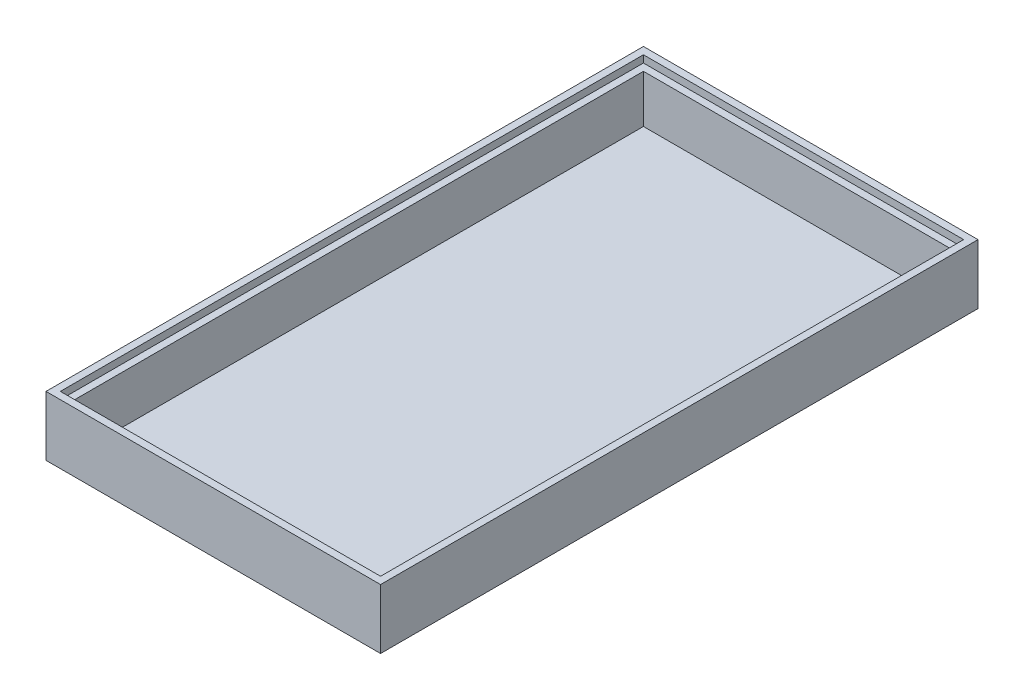
SolidWorks part; units mm, degrees
ref_plane "Front Plane" through (0, 0, 0) normal (0, 0, 1) x (1, 0, 0)
ref_plane "Top Plane" through (0, 0, 0) normal (0, 1, 0) x (1, 0, 0)
ref_plane "Right Plane" through (0, 0, 0) normal (1, 0, 0) x (0, 0, -1)
sketch "Sketch1" plane through (0, 0, 0) normal (0, 1, 0) x (1, 0, 0)
  line L1 (70, -125) -> (-70, -125)
  line L2 (70, -125) -> (70, 125)
  line L3 (70, 125) -> (-70, 125)
  line L4 (-70, -125) -> (-70, 125)
  line L5 (70, -125) -> (-70, 125) construction
  line L6 (70, 125) -> (-70, -125) construction
  point P0 (0, 0)
  dimension "D1" = 250
  dimension "D2" = 140
extrude "Boss-Extrude1" add sketch "Sketch1" along normal blind 25
ref_plane "Plane1" through (0, 25, 0) normal (0, 1, 0) x (1, 0, 0)
sketch "Sketch2" plane through (0, 25, 0) normal (0, 1, 0) x (1, 0, 0)
  line L1 (64, -119) -> (-64, -119)
  line L2 (64, -119) -> (64, 119)
  line L3 (64, 119) -> (-64, 119)
  line L4 (-64, -119) -> (-64, 119)
  line L5 (64, -119) -> (-64, 119) construction
  line L6 (64, 119) -> (-64, -119) construction
  point P0 (0, 0)
  dimension "D1" = 128
  dimension "D2" = 238
extrude "Cut-Extrude1" cut sketch "Sketch2" against normal blind 23
ref_plane "Plane2" through (0, 2, 0) normal (0, 1, 0) x (1, 0, 0)
ref_plane "Plane3" through (0, 25, 0) normal (0, 1, 0) x (1, 0, 0)
sketch "Sketch4" plane through (0, 25, 0) normal (0, 1, 0) x (1, 0, 0)
  line L1 (67, 122) -> (-67, 122)
  line L2 (67, 122) -> (67, -122)
  line L3 (67, -122) -> (-67, -122)
  line L4 (-67, 122) -> (-67, -122)
  line L5 (67, 122) -> (-67, -122) construction
  line L6 (67, -122) -> (-67, 122) construction
  point P0 (0, 0)
  dimension "D1" = 134
  dimension "D2" = 244
extrude "Cut-Extrude2" cut sketch "Sketch4" against normal blind 3
